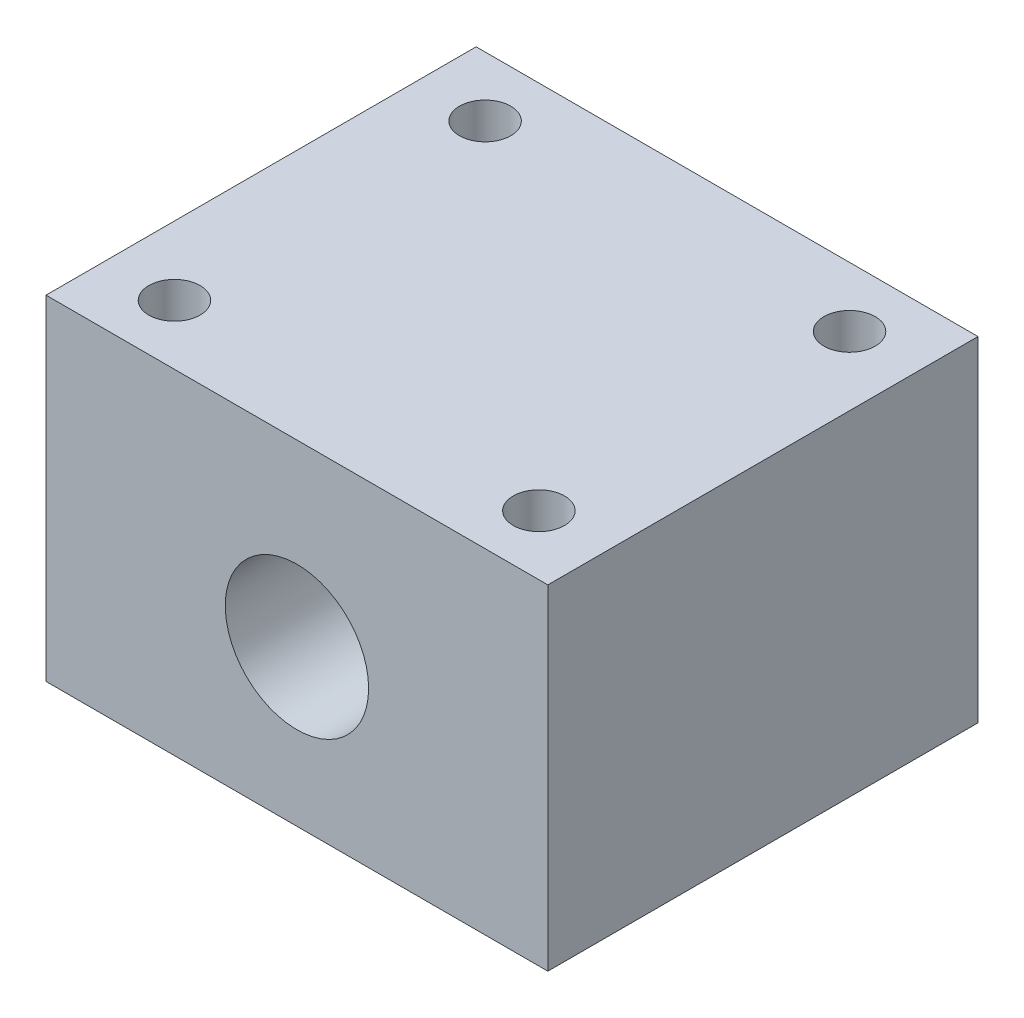
SolidWorks part; units mm, degrees
ref_plane "Front Plane" through (0, 0, 0) normal (0, 0, 1) x (1, 0, 0)
ref_plane "Top Plane" through (0, 0, 0) normal (0, 1, 0) x (1, 0, 0)
ref_plane "Right Plane" through (0, 0, 0) normal (1, 0, 0) x (0, 0, -1)
sketch "Sketch1" plane through (0, 0, 0) normal (0, 0, 1) x (1, 0, 0)
  line L1 (-21, 15) -> (21, 15)
  line L2 (-21, 15) -> (-21, -13)
  line L3 (-21, -13) -> (21, -13)
  line L4 (21, 15) -> (21, -13)
  circle A0 centre (0, 0) radius 6
  dimension "D1" = 12
  dimension "D2" = 42
  dimension "D3" = 28
  dimension "D4" = 15
  dimension "D5" = 21
extrude "Boss-Extrude1" add sketch "Sketch1" along normal blind 36
sketch "Sketch2" plane through (0, 15, 0) normal (0, 1, 0) x (1, 0, 0)
  line L0 (21, -36) -> (21, 0) construction
  line L1 (21, 0) -> (-21, 0) construction
  circle A0 centre (-15.25, -5) radius 2.1463
  circle A1 centre (15.25, -5) radius 2.1463
  circle A2 centre (15.25, -31) radius 2.1463
  circle A3 centre (-15.25, -31) radius 2.1463
  dimension "D9" = 4.2926
  dimension "D10" = 4.2926
  dimension "D11" = 4.2926
  dimension "D12" = 4.2926
  dimension "D1" = 30.5
  dimension "D2" = 30.5
  dimension "D3" = 5.75
  dimension "D4" = 5.75
  dimension "D5" = 26
  dimension "D6" = 26
  dimension "D7" = 5
  dimension "D8" = 5
extrude "Cut-Extrude1" cut sketch "Sketch2" against normal through all
